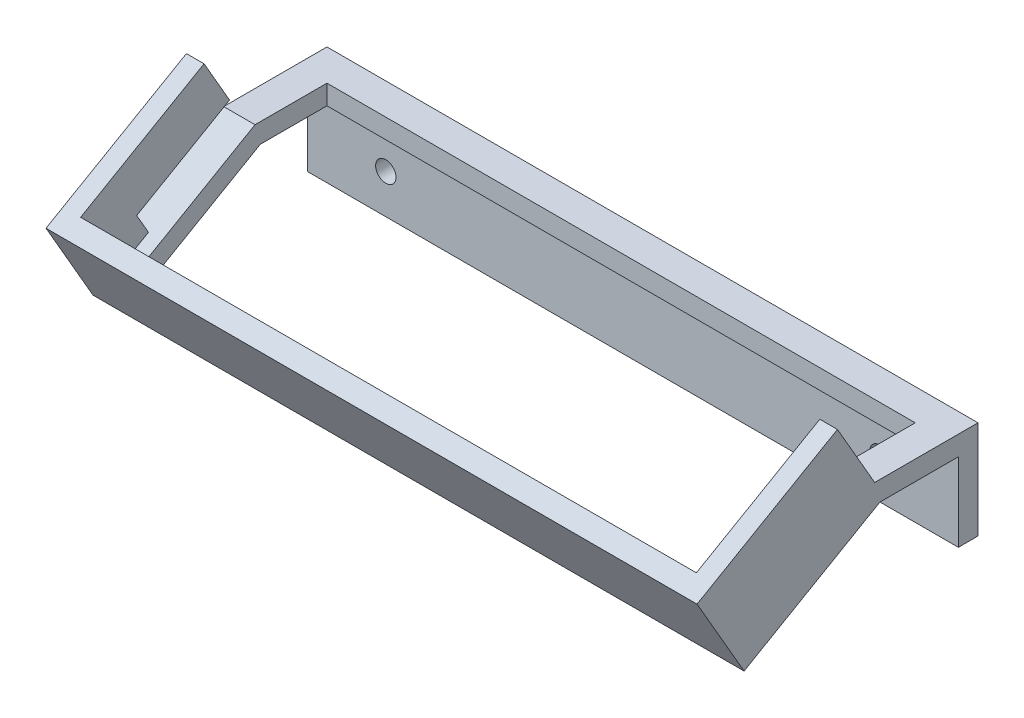
SolidWorks part; units mm, degrees
ref_plane "Front Plane" through (0, 0, 0) normal (0, 0, 1) x (1, 0, 0)
ref_plane "Top Plane" through (0, 0, 0) normal (0, 1, 0) x (1, 0, 0)
ref_plane "Right Plane" through (0, 0, 0) normal (1, 0, 0) x (0, 0, -1)
sketch "Sketch1" plane through (0, 0, 0) normal (1, 0, 0) x (0, 0, -1)
  line L0 (0, 0) -> (0, 20)
  line L1 (0, 20) -> (-20, 20)
  line L4 (-20, 20) -> (-54.641, 0)
  line L5 (-54.641, 0) -> (-66.641, 20.7846)
  line L6 (5, 0) -> (5, 25)
  line L7 (5, 25) -> (-21.3397, 25)
  line L8 (-21.3397, 25) -> (-52.8109, 6.8301)
  line L9 (-52.8109, 6.8301) -> (-62.3109, 23.2846)
  line L10 (-66.641, 20.7846) -> (-62.3109, 23.2846)
  line L11 (0, 0) -> (5, 0)
  dimension "D1" = 20
  dimension "D2" = 20
  dimension "D3" = 60
  dimension "D4" = 5
  dimension "D5" = 19
extrude "Boss-Extrude1" add sketch "Sketch1" along normal mid plane 166
sketch "Sketch2" plane through (0, 27.9904, 16.1603) normal (0, 0.866, 0.5) x (1, 0, 0)
  line L1 (-83, -5.9808) -> (-78.5, -5.9808)
  line L2 (-83, -5.9808) -> (-83, -42.3205)
  line L3 (-83, -42.3205) -> (-78.5, -42.3205)
  line L4 (-78.5, -5.9808) -> (-78.5, -42.3205)
  line L5 (83, -42.3205) -> (-83, -42.3205) construction
  line L7 (83, -5.9808) -> (78.5, -5.9808)
  line L8 (83, -5.9808) -> (83, -42.3205)
  line L9 (83, -42.3205) -> (78.5, -42.3205)
  line L10 (78.5, -5.9808) -> (78.5, -42.3205)
  dimension "D1" = 36.3397
  dimension "D2" = 4.5
  dimension "D3" = 36.3397
  dimension "D4" = 4.5
extrude "Boss-Extrude2" add sketch "Sketch2" along normal blind 19
sketch "Sketch3" plane through (0, 25, 0) normal (0, 1, 0) x (1, 0, 0)
  line L0 (83, 5) -> (83, -21.3397) construction
  line L1 (83, 5) -> (-83, 5) construction
  line L2 (-83, 5) -> (-83, -21.3397) construction
  line L3 (83, 5) -> (83, -21.3397)
  line L4 (83, 5) -> (-83, 5)
  line L5 (-83, 5) -> (-83, -21.3397)
  line L6 (75, -3) -> (75, -21.3397)
  line L7 (75, -3) -> (-75, -3)
  line L8 (-75, -3) -> (-75, -21.3397)
  line L9 (-75, -21.3397) -> (75, -21.3397)
  point P8 (0, 0)
  line M4 (-78.5, -21.3397) -> (78.5, -21.3397)
  dimension "D1" = 8
extrude "Cut-Extrude1" cut sketch "Sketch3" against normal blind 6 contours L7 L8 L6 M4
sketch "Sketch4" plane through (0, 27.9904, 16.1603) normal (0, 0.866, 0.5) x (1, 0, 0)
  line L1 (-75, -5.9808) -> (75, -5.9808)
  line L2 (-75, -5.9808) -> (-75, -37.3208)
  line L3 (-75, -37.3208) -> (75, -37.3208)
  line L4 (75, -5.9808) -> (75, -37.3208)
  dimension "D1" = 31.34
  dimension "D2" = 150
extrude "Cut-Extrude2" cut sketch "Sketch4" against normal blind 5
sketch "Sketch5" plane through (-83, 0, 0) normal (-1, 0, 0) x (0, 0, 1)
  line L0 (21.3397, 25) -> (45.0169, 11.33)
  line L1 (21.3397, 25) -> (24.3397, 30.1962)
  line L2 (30.8397, 41.4545) -> (21.3397, 25) construction
  line L3 (24.3397, 30.1962) -> (48.0169, 16.5262)
  line L4 (48.0169, 16.5262) -> (45.0169, 11.33)
  dimension "D3" = 90
  dimension "D1" = 27.34
  dimension "D2" = 6
extrude "Cut-Extrude3" cut sketch "Sketch5" against normal blind 5
sketch "Sketch6" plane through (0, 0, -5) normal (0, 0, -1) x (-1, 0, 0)
  line L0 (-83, 0) -> (-83, 25) construction
  line L1 (83, 0) -> (83, 25) construction
  line L2 (-83, 0) -> (83, 0) construction
  circle A0 centre (-63, 10) radius 2.6
  circle A1 centre (63, 10) radius 2.6
  point P10 (0, 0)
  dimension "D1" = 5.2
  dimension "D2" = 5.2
  dimension "D3" = 20
  dimension "D4" = 20
  dimension "D5" = 10
extrude "Cut-Extrude4" cut sketch "Sketch6" against normal blind 5
